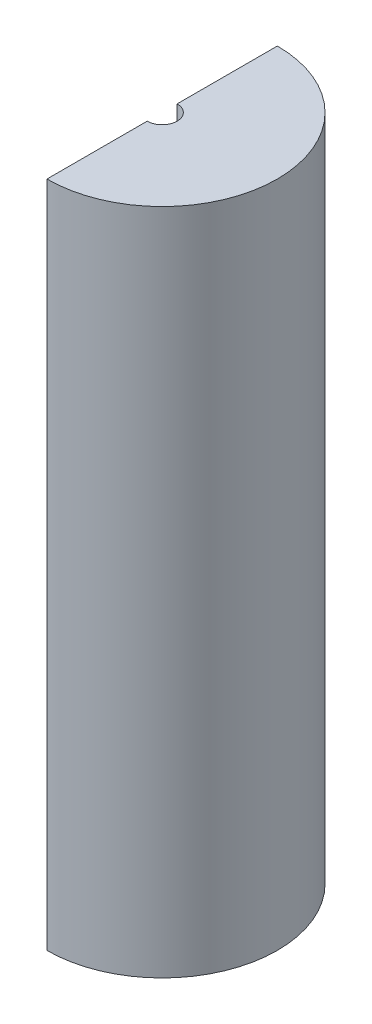
SolidWorks part; units mm, degrees
ref_plane "Front Plane" through (0, 0, 0) normal (0, 0, 1) x (1, 0, 0)
ref_plane "Top Plane" through (0, 0, 0) normal (0, 1, 0) x (1, 0, 0)
ref_plane "Right Plane" through (0, 0, 0) normal (1, 0, 0) x (0, 0, -1)
sketch "Sketch1" plane through (0, 0, 0) normal (0, 1, 0) x (1, 0, 0)
  line L7 (0, 0) -> (0, 0.3)
  line L8 (0, 0.3898) -> (0, 0.6898)
  line L9 (0, 0.3898) -> (0, 0.3) construction
  line L10 (0.0449, 0.3449) -> (0, 0.15) construction
  line L11 (0.0449, 0.3449) -> (0, 0.5398) construction
  arc A0 (0, 0) -> (0, 0.6898) centre (0, 0.3449) ccw
  arc A2 (0, 0.3) -> (0, 0.3898) centre (0, 0.3449) ccw
  dimension "D1" = 0.3
  dimension "D2" = 0.3
  dimension "D4" = 0.2
  dimension "D3" = 180
extrude "Boss-Extrude1" add sketch "Sketch1" along normal blind 2
equation "\"t\"= 0.3'thickness of the sheets"
equation "\"FlexJoint\"= 0.15'Width of flextures"
equation "\"FoldJoint\"= 0.4'Width of folding joints"
equation "\"AssembleAngle\"= 90'Angle of assembly parts"
equation "\"D1@Sketch1\"=\"t\""
equation "\"D2@Sketch1\"=\"t\""
equation "\"D4@Sketch1\"=\"FoldJoint\"/2"
equation "\"D3@Sketch1\"=\"AssembleAngle\"+90"
